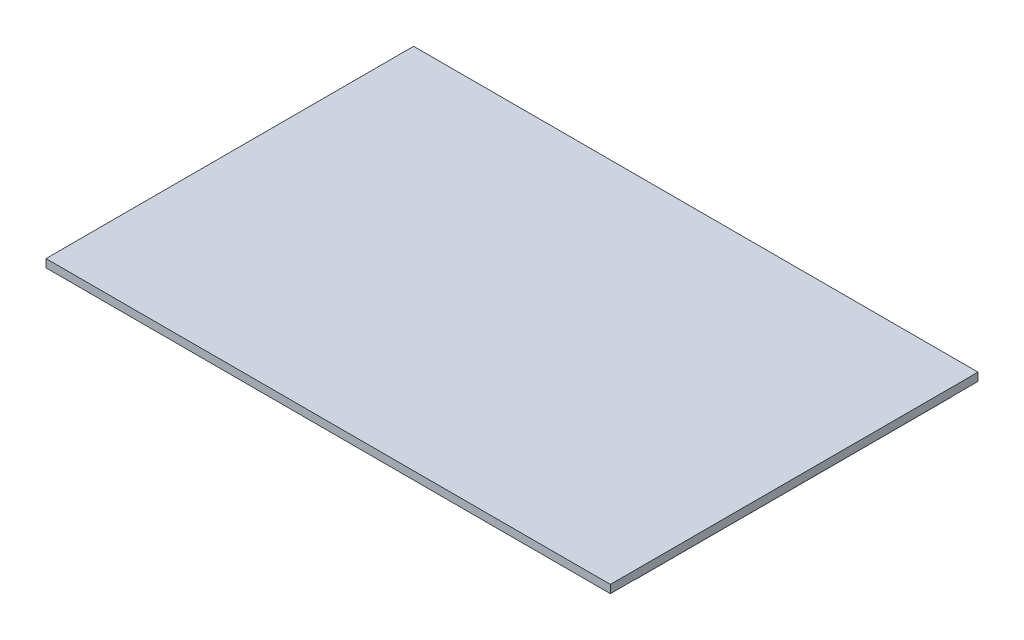
SolidWorks part; units mm, degrees
material "A-Glass Fiber"
ref_plane "Front Plane" through (0, 0, 0) normal (0, 0, 1) x (1, 0, 0)
ref_plane "Top Plane" through (0, 0, 0) normal (0, 1, 0) x (1, 0, 0)
ref_plane "Right Plane" through (0, 0, 0) normal (1, 0, 0) x (0, 0, -1)
sketch "Sketch1" plane through (0, 0, 0) normal (0, 1, 0) x (1, 0, 0)
  line L1 (0, 0) -> (111.125, 0)
  line L2 (0, 0) -> (0, 72.39)
  line L3 (0, 72.39) -> (111.125, 72.39)
  line L4 (111.125, 0) -> (111.125, 72.39)
  dimension "D1" = 111.125
  dimension "D2" = 72.39
extrude "Boss-Extrude1" add sketch "Sketch1" along normal blind 1.5875
sketch "Sketch2" plane through (0, 0, 0) normal (0, -1, 0) x (1, 0, 0)
  line L0 (0, -72.39) -> (0, 0) construction
  line L1 (0, -5.08) -> (111.125, -5.08)
  line L2 (0, -5.08) -> (0, -67.31)
  line L3 (0, -67.31) -> (111.125, -67.31)
  line L4 (111.125, -5.08) -> (111.125, -67.31)
  line L5 (111.125, 0) -> (111.125, -72.39) construction
  line L6 (0, 0) -> (111.125, 0) construction
  line L7 (111.125, -72.39) -> (0, -72.39) construction
  dimension "D1" = 5.08
  dimension "D2" = 5.08
extrude "Boss-Extrude2" add sketch "Sketch2" along normal blind 0.0508 separate body
